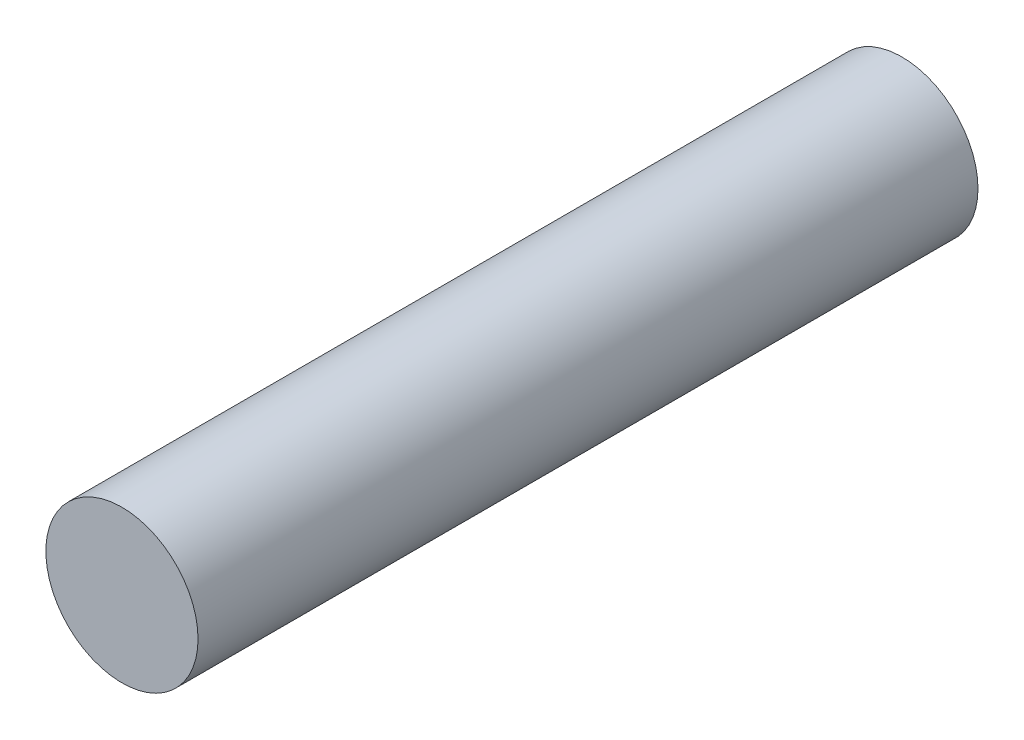
SolidWorks part; units mm, degrees
ref_plane "前视基准面" through (0, 0, 0) normal (0, 0, 1) x (1, 0, 0)
ref_plane "上视基准面" through (0, 0, 0) normal (0, 1, 0) x (1, 0, 0)
ref_plane "右视基准面" through (0, 0, 0) normal (1, 0, 0) x (0, 0, -1)
other "Configuration Table"
sketch "草图1" plane through (0, 0, 0) normal (0, 0, 1) x (1, 0, 0)
  circle A0 centre (0, 0) radius 2
  dimension "diameter" = 4
extrude "Cable_envelope" add sketch "草图1" along normal blind 20.5
